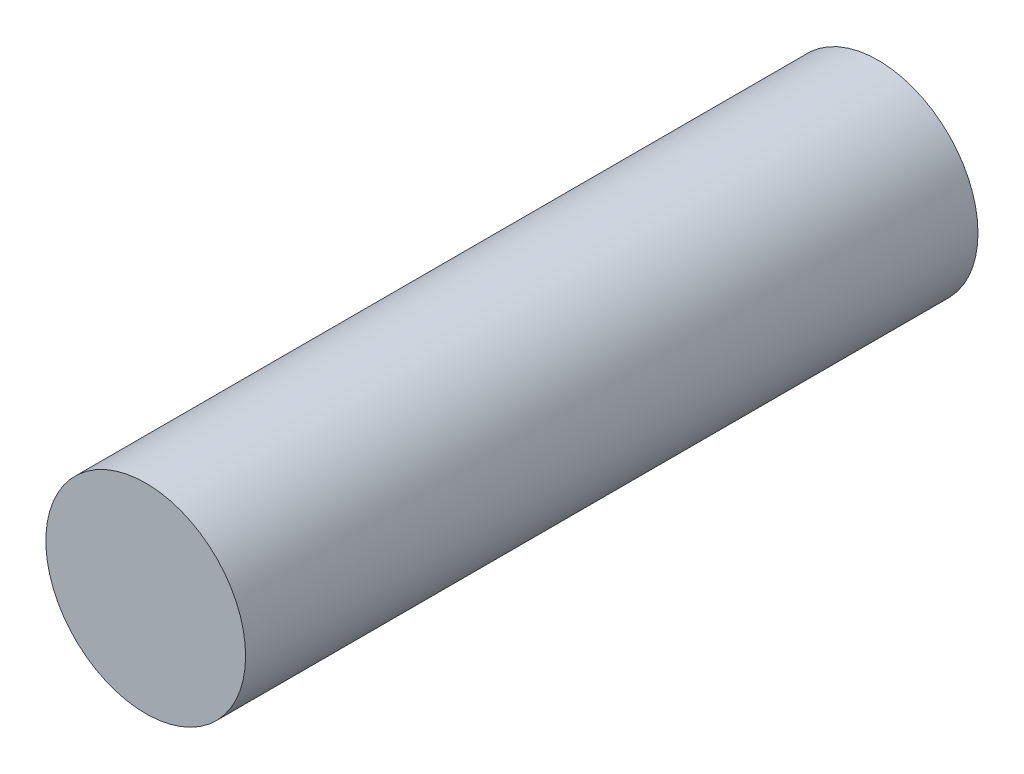
SolidWorks part; units mm, degrees
ref_plane "Płaszczyzna przednia" through (0, 0, 0) normal (0, 0, 1) x (1, 0, 0)
ref_plane "Płaszczyzna górna" through (0, 0, 0) normal (0, 1, 0) x (1, 0, 0)
ref_plane "Płaszczyzna prawa" through (0, 0, 0) normal (1, 0, 0) x (0, 0, -1)
sketch "Szkic1" plane through (0, 0, 0) normal (0, 0, 1) x (1, 0, 0)
  circle A0 centre (0, 0) radius 1.5
extrude "Dodanie-wyciągnięcie1" add sketch "Szkic1" along normal blind 11
